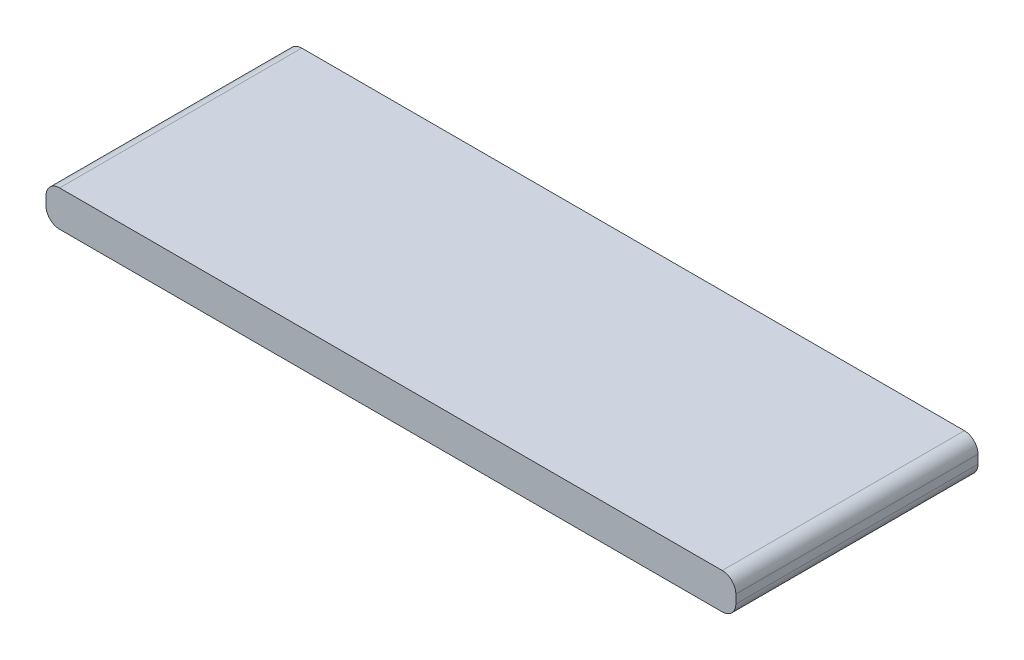
SolidWorks part; units mm, degrees
material "ABS"
ref_plane "X-Y Datum" through (0, 0, 0) normal (0, 0, 1) x (1, 0, 0)
ref_plane "X-Z Datum" through (0, 0, 0) normal (0, 1, 0) x (1, 0, 0)
ref_plane "Y-Z Datum" through (0, 0, 0) normal (1, 0, 0) x (0, 0, -1)
sketch "Sketch2" plane through (0, 0, 0) normal (0, 0, 1) x (1, 0, 0)
  line L6 (152.4, 7.9241) -> (0, 7.9241)
  line L7 (152.4, 7.9241) -> (152.4, 0)
  line L8 (152.4, 0) -> (0, 0)
  line L9 (0, 7.9241) -> (0, 0)
  dimension "D1" = 152.4
extrude "Boss-Extrude1" add sketch "Sketch2" along normal blind 53.5
fillet "Fillet1" radius 3 4 edges at (152.4, 7.9241, 26.75) (152.4, 0, 26.75) (0, 7.9241, 26.75) (0, 0, 26.75)
